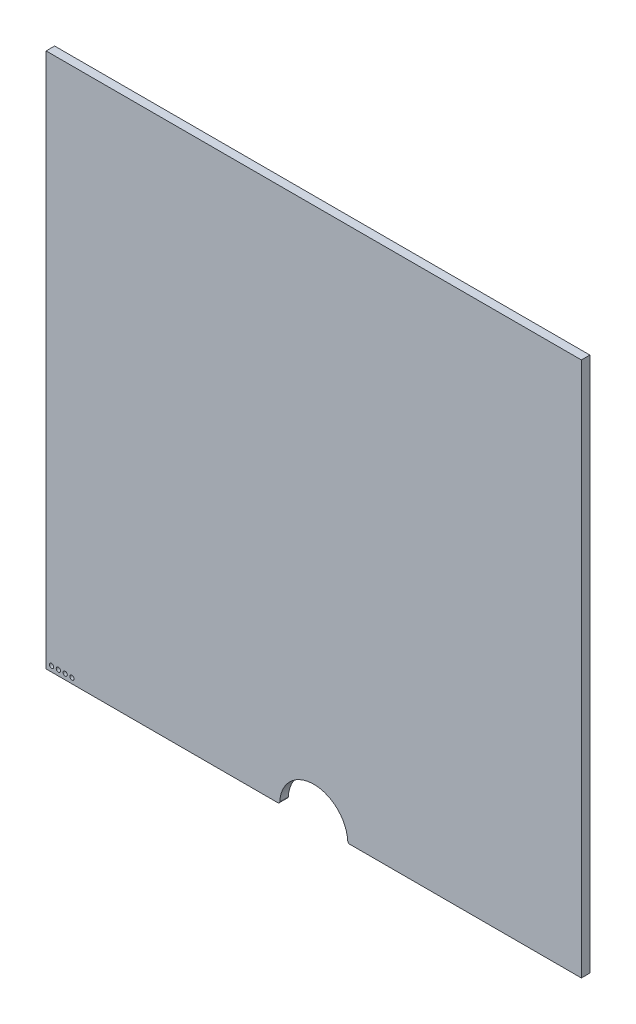
SolidWorks part; units mm, degrees
material "PVC Rigid"
ref_plane "Front Plane" through (0, 0, 0) normal (0, 0, 1) x (1, 0, 0)
ref_plane "Top Plane" through (0, 0, 0) normal (0, 1, 0) x (1, 0, 0)
ref_plane "Right Plane" through (0, 0, 0) normal (1, 0, 0) x (0, 0, -1)
sketch "Sketch1" plane through (0, 0, 0) normal (0, 0, 1) x (1, 0, 0)
  line L1 (0, 0) -> (200, 0)
  line L2 (0, 0) -> (0, 200)
  line L3 (0, 200) -> (200, 200)
  line L4 (200, 0) -> (200, 200)
  dimension "D1" = 200
extrude "Boss-Extrude1" add sketch "Sketch1" along normal blind 3.175
sketch "Sketch5" plane through (0, 0, 3.175) normal (0, 0, 1) x (1, 0, 0)
  line L0 (200, 0) -> (200, 200) construction
  line L1 (0, 0) -> (200, 0) construction
  line L2 (0, 200) -> (0, 0) construction
  line L3 (200, 200) -> (0, 200) construction
  line L4 (200, 0) -> (200, 200)
  line L5 (0, 0) -> (200, 0)
  line L6 (0, 200) -> (0, 0)
  line L7 (200, 200) -> (0, 200)
  line L8 (199.9492, 0.0508) -> (199.9492, 199.9492)
  line L9 (199.9492, 199.9492) -> (0.0508, 199.9492)
  line L10 (0.0508, 199.9492) -> (0.0508, 0.0508)
  line L11 (0.0508, 0.0508) -> (199.9492, 0.0508)
  dimension "D1" = 0.0508
extrude "Cut-Extrude2" cut sketch "Sketch5" against normal through all
sketch "Sketch2" plane through (0, 0, 3.175) normal (0, 0, 1) x (1, 0, 0)
  line L1 (87.3, 0.0508) -> (112.7, 0.0508)
  line L2 (0.0508, 0.0508) -> (199.9492, 0.0508) construction
  line L3 (100, 199.9492) -> (100, 0.0508) construction
  line L4 (199.9492, 199.9492) -> (0.0508, 199.9492) construction
  arc A0 (112.7, 0.0508) -> (87.3, 0.0508) centre (100, 0.0508) ccw
  dimension "D1" = 25.4
extrude "Cut-Extrude1" cut sketch "Sketch2" against normal blind 3.175
fillet "Fillet1" radius 0.7937 2 edges at (87.3, 0.0508, 1.5875) (112.7, 0.0508, 1.5875)
sketch "Sketch6" plane through (0, 0, 3.175) normal (0, 0, 1) x (1, 0, 0)
  line L0 (0.0508, 199.9492) -> (0.0508, 0.0508) construction
  line L1 (0.0508, 0.0508) -> (86.5296, 0.0508) construction
  circle A0 centre (2.0828, 2.0828) radius 0.7938
  dimension "D1" = 1.5875
  dimension "D2" = 2.032
  dimension "D3" = 2.032
extrude "Cut-Extrude3" cut sketch "Sketch6" against normal blind 1.27
pattern_linear "LPattern1" count 4 spacing 2.54 along (1, 0, 0) of "Cut-Extrude3"
